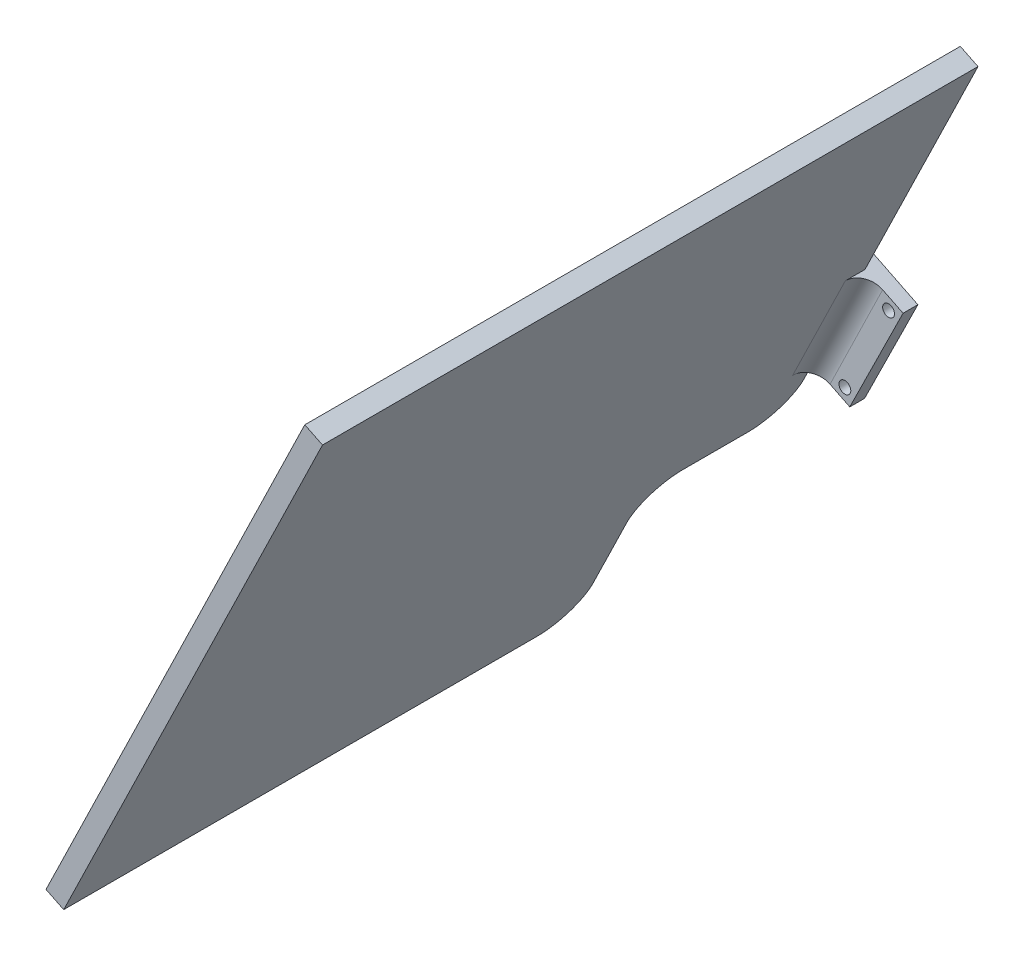
SolidWorks part; units mm, degrees
ref_plane "前视基准面" through (0, 0, 0) normal (0, 0, 1) x (1, 0, 0)
ref_plane "上视基准面" through (0, 0, 0) normal (0, 1, 0) x (1, 0, 0)
ref_plane "右视基准面" through (0, 0, 0) normal (1, 0, 0) x (0, 0, -1)
other "Configuration Table"
sketch "草图1" plane through (0, 0, 0) normal (0, 0, 1) x (1, 0, 0)
  line L0 (-67.5746, 2.2354) -> (-78.389, -19.6371)
  line L1 (-67.5746, 2.2354) -> (-45.7027, -8.5787)
  line L2 (-78.389, -19.6371) -> (-56.5172, -30.4512)
  line L3 (-45.7027, -8.5787) -> (-56.5172, -30.4512)
  circle A0 centre (-66.5775, -0.7118) radius 1.2
  circle A1 centre (-75.4419, -18.6401) radius 1.2
  circle A2 centre (-57.5136, -27.5044) radius 1.2
  circle A3 centre (-48.6492, -9.5761) radius 1.2
extrude "凸台-拉伸1" add sketch "草图1" along normal blind 3
sketch "草图2" plane through (0, 0, 3) normal (0, 0, 1) x (1, 0, 0)
  line L0 (-86.6066, -63.7835) -> (-51.6013, 8.1513) construction
  line L1 (-86.6066, -63.7835) -> (-34.0986, 44.1187)
  line L2 (-86.6066, -63.7835) -> (-83.0099, -65.5338)
  line L3 (-34.0986, 44.1187) -> (-30.5018, 42.3685)
  line L4 (-83.0099, -65.5338) -> (-30.5018, 42.3685)
  point P2 (0, 0)
  point P4 (0, 0)
extrude "凸台-拉伸2" add sketch "草图2" along normal blind 133
fillet "圆角1" radius 4 2 edges at (-62.3581, -13.9536, 3) (-58.7723, -15.7265, 3)
sketch "草图4" plane through (-44.9286, 21.8634, 0) normal (-0.8992, 0.4376, 0) x (0, 0, 1)
  line L0 (3, -63.8263) -> (32.0773, -63.8263)
  line L1 (3, -52.0329) -> (3, -95.2495) construction
  line L2 (32.0773, -63.8263) -> (32.0773, -95.2495)
  line L3 (136, -95.2495) -> (3, -95.2495) construction
  line L4 (3, -63.8263) -> (3, -95.2495)
  line L5 (3, -95.2495) -> (32.0773, -95.2495)
extrude "切除-拉伸1" cut sketch "草图4" against normal blind 4
fillet "圆角3" radius 8 3 edges at (-71.0585, -36.4034, 3) (-71.0585, -36.4034, 32.0773) (-84.8083, -64.6587, 32.0773)
